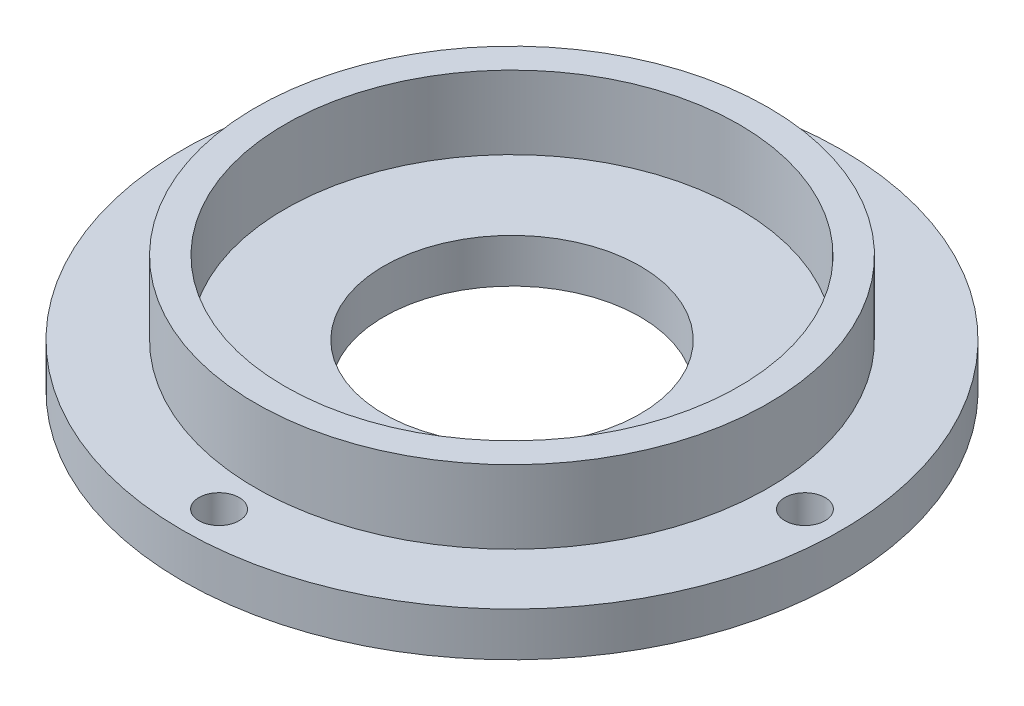
SolidWorks part; units mm, degrees
material "Liga 1060"
ref_plane "Plano frontal" through (0, 0, 0) normal (0, 0, 1) x (1, 0, 0)
ref_plane "Plano superior" through (0, 0, 0) normal (0, 1, 0) x (1, 0, 0)
ref_plane "Plano direito" through (0, 0, 0) normal (1, 0, 0) x (0, 0, -1)
sketch "Esboço1" plane through (0, 0, 0) normal (0, 0, 1) x (1, 0, 0)
  line L0 (0, 0) -> (0, 20) construction
  line L1 (17.5, 0) -> (17.5, 6)
  line L2 (17.5, 6) -> (31, 6)
  line L3 (31, 6) -> (31, 16)
  line L4 (31, 16) -> (35, 16)
  line L5 (35, 16) -> (35, 6)
  line L6 (35, 6) -> (45, 6)
  line L7 (45, 6) -> (45, 0)
  line L8 (45, 0) -> (17.5, 0)
  dimension "D1" = 35
  dimension "D2" = 62
  dimension "D3" = 10
  dimension "D4" = 6
  dimension "D6" = 4
  dimension "D7" = 10
revolve "Revolução1" add sketch "Esboço1" angle 360 about L0
hole_wizard "Furo com folga de M51" positions "Esboço3" profile "Esboço4" hole size "M5" standard "ISO" end condition through all
sketch "Esboço3" plane through (0, 6, 0) normal (0, 1, 0) x (1, 0, 0)
  circle A1 centre (0, 0) radius 40 construction
  point P0 (0, 40)
  point P2 (40, 0)
  point P4 (0, -40)
  point P6 (-40, 0)
  dimension "D1" = 80
sketch "Esboço4" plane through (0, 6, -40) normal (1, 0, 0) x (0, 0, 1)
  line L0 (0, 0) -> (0, 6)
  line L1 (0, 6) -> (2.75, 6)
  line L2 (2.75, 6) -> (2.75, 0)
  line L5 (2.75, 0) -> (0, 0)
  line L11 (0, -6.35) -> (0, 107.95) construction
  dimension "Thru Hole Dia." = 5.5
  dimension "Thru Hole Depth" = 6
